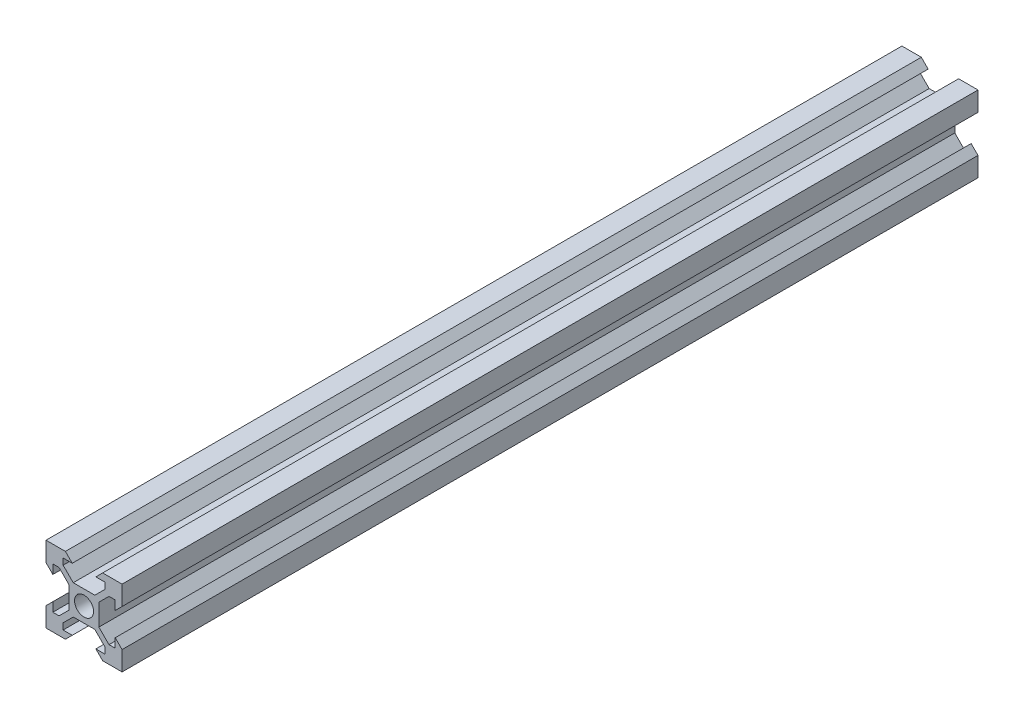
SolidWorks part; units mm, degrees
ref_plane "Front Plane" through (0, 0, 0) normal (0, 0, 1) x (1, 0, 0)
ref_plane "Top Plane" through (0, 0, 0) normal (0, 1, 0) x (1, 0, 0)
ref_plane "Right Plane" through (0, 0, 0) normal (1, 0, 0) x (0, 0, -1)
sketch "Sketch1" plane through (0, 0, 0) normal (0, 0, 1) x (1, 0, 0)
  line L0 (0, 19.8963) -> (0, -21.0662) construction
  line L1 (-23.9511, 0) -> (36.3898, 0) construction
  line L2 (0, 0) -> (-35.2594, 35.2594) construction
  line L3 (0, 0) -> (35.2594, 35.2594) construction
  line L4 (2.8393, 3.9) -> (-2.8393, 3.9)
  line L5 (-2.8393, 3.9) -> (-5.5, 6.5607)
  line L6 (-5.5, 6.5607) -> (-5.5, 8.2)
  line L7 (-5.5, 8.2) -> (-3.1, 8.2)
  line L8 (-3.1, 8.2) -> (-4.9, 10)
  line L9 (-4.9, 10) -> (-10, 10)
  line L10 (-10, 4.9) -> (-10, 10)
  line L11 (-8.2, 3.1) -> (-10, 4.9)
  line L12 (-8.2, 5.5) -> (-8.2, 3.1)
  line L13 (-6.5607, 5.5) -> (-8.2, 5.5)
  line L14 (-3.9, 2.8393) -> (-6.5607, 5.5)
  line L15 (-3.9, -2.8393) -> (-3.9, 2.8393)
  line L16 (3.1, 8.2) -> (4.9, 10)
  line L17 (5.5, 8.2) -> (3.1, 8.2)
  line L18 (4.9, 10) -> (10, 10)
  line L19 (10, 4.9) -> (10, 10)
  line L20 (8.2, 3.1) -> (10, 4.9)
  line L21 (8.2, 5.5) -> (8.2, 3.1)
  line L22 (6.5607, 5.5) -> (8.2, 5.5)
  line L23 (5.5, 6.5607) -> (5.5, 8.2)
  line L24 (2.8393, 3.9) -> (5.5, 6.5607)
  line L25 (3.9, 2.8393) -> (6.5607, 5.5)
  line L26 (3.9, -2.8393) -> (3.9, 2.8393)
  line L27 (-3.9, -2.8393) -> (-6.5607, -5.5)
  line L28 (-6.5607, -5.5) -> (-8.2, -5.5)
  line L29 (-8.2, -5.5) -> (-8.2, -3.1)
  line L30 (-8.2, -3.1) -> (-10, -4.9)
  line L31 (-10, -4.9) -> (-10, -10)
  line L32 (-4.9, -10) -> (-10, -10)
  line L33 (-3.1, -8.2) -> (-4.9, -10)
  line L34 (-5.5, -6.5607) -> (-5.5, -8.2)
  line L35 (-5.5, -8.2) -> (-3.1, -8.2)
  line L36 (-2.8393, -3.9) -> (-5.5, -6.5607)
  line L37 (2.8393, -3.9) -> (-2.8393, -3.9)
  line L38 (2.8393, -3.9) -> (5.5, -6.5607)
  line L39 (3.9, -2.8393) -> (6.5607, -5.5)
  line L40 (6.5607, -5.5) -> (8.2, -5.5)
  line L41 (5.5, -6.5607) -> (5.5, -8.2)
  line L42 (5.5, -8.2) -> (3.1, -8.2)
  line L43 (3.1, -8.2) -> (4.9, -10)
  line L44 (4.9, -10) -> (10, -10)
  line L45 (10, -4.9) -> (10, -10)
  line L46 (8.2, -5.5) -> (8.2, -3.1)
  line L47 (8.2, -3.1) -> (10, -4.9)
  circle A0 centre (0, 0) radius 2.5
  point P37 (0, 3.9)
  point P40 (-3.9, 0)
  point P53 (3.9, 0)
  dimension "D2" = 5
  dimension "D1" = 6.2
  dimension "D3" = 1.8
  dimension "D4" = 11
  dimension "D5" = 45
  dimension "D6" = 6.1
  dimension "D7" = 1.5
  dimension "D8" = 20
extrude "Boss-Extrude1" add sketch "Sketch1" along normal blind 225
